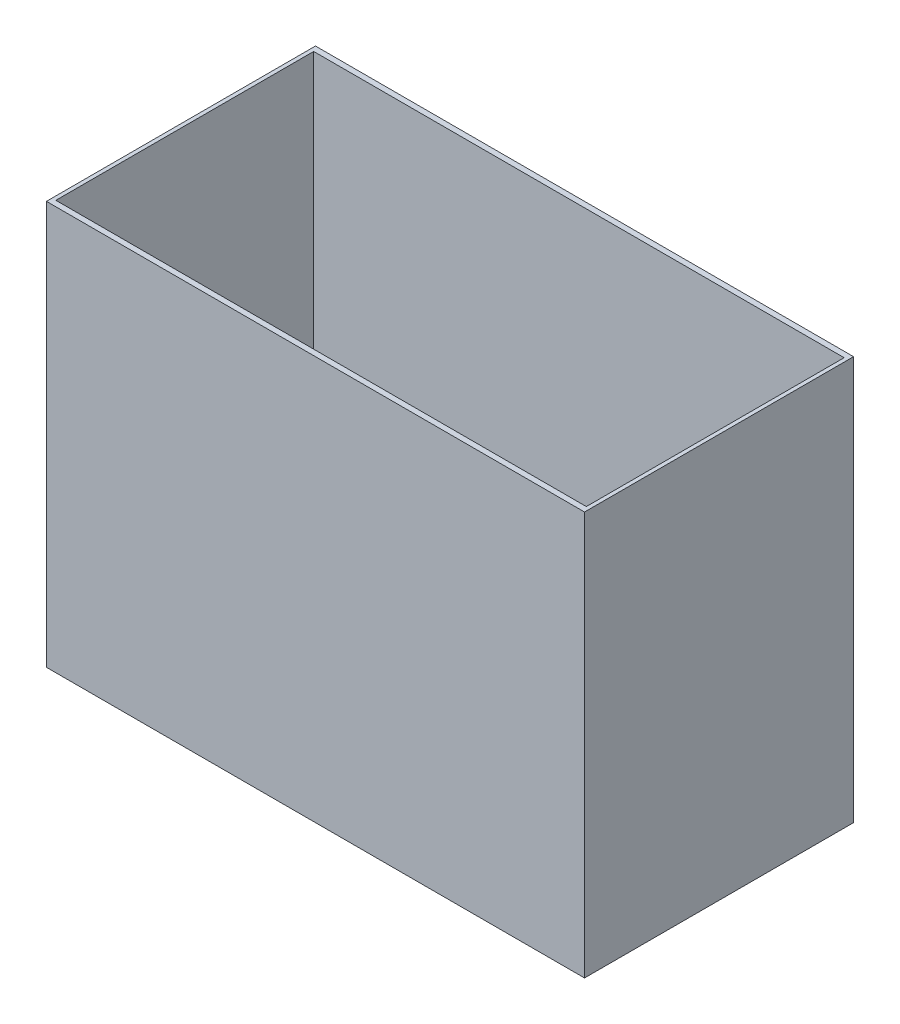
SolidWorks part; units mm, degrees
ref_plane "Front Plane" through (0, 0, 0) normal (0, 0, 1) x (1, 0, 0)
ref_plane "Top Plane" through (0, 0, 0) normal (0, 1, 0) x (1, 0, 0)
ref_plane "Right Plane" through (0, 0, 0) normal (1, 0, 0) x (0, 0, -1)
other "Bounding Box"
ref_plane "Default Plane" through (-292.1, 0, -139.7) normal (0, 1, 0) x (1, 0, 0)
sketch "Sketch1" plane through (0, 0, 0) normal (0, 1, 0) x (1, 0, 0)
  line L0 (-292.1, -139.7) -> (165.1, -139.7) construction
  line L5 (292.1, 139.7) -> (165.1, 139.7)
  line L6 (292.1, 139.7) -> (292.1, -139.7)
  line L7 (292.1, -139.7) -> (165.1, -139.7)
  line L8 (165.1, 139.7) -> (165.1, -139.7)
  dimension "D1" = 127
extrude "Boss-Extrude1" add sketch "Sketch1" along normal blind 6.35
sketch "Sketch2" plane through (0, 6.35, 0) normal (0, 1, 0) x (1, 0, 0)
  line L0 (-245.9259, -63.5) -> (-55.3589, -63.5) construction
  line L1 (342.9, -120.6497) -> (431.8, -120.6497)
  line L2 (342.9, -120.6497) -> (342.9, -101.5997)
  line L3 (342.9, -101.5997) -> (431.8, -101.5997)
  line L4 (431.8, -120.6497) -> (431.8, -101.5997)
  line L5 (342.9, -120.6497) -> (431.8, -101.5997) construction
  line L6 (342.9, -101.5997) -> (431.8, -120.6497) construction
  line L7 (292.1, 139.7) -> (292.1, -139.7) construction
  line L8 (292.1, 0) -> (165.1, 0) construction
  line L9 (165.1, -139.7) -> (165.1, 139.7) construction
  line L10 (228.6, 0) -> (228.6, 121.6784) construction
  line L11 (114.3, -101.5997) -> (25.4, -120.6497) construction
  line L12 (114.3, -120.6497) -> (25.4, -101.5997) construction
  line L13 (25.4, -120.6497) -> (25.4, -101.5997)
  line L14 (114.3, -101.5997) -> (25.4, -101.5997)
  line L15 (114.3, -120.6497) -> (114.3, -101.5997)
  line L16 (114.3, -120.6497) -> (25.4, -120.6497)
  point P0 (387.35, -111.1247)
  point P17 (69.85, -111.1247)
  dimension "D1" = 19.05
  dimension "D2" = 88.9
  dimension "D3" = 38.0997
  dimension "D4" = 50.8
  dimension "D5" = 63.5
extrude "Boss-Extrude2" [suppressed] add sketch "Sketch2" along normal blind 304.8 separate body contours L2 L1 L4 L3
pattern_linear "LPattern1" [suppressed] count 2 spacing 304.8
pattern_linear "LPattern2" [suppressed] count 2 spacing 215.9
sketch "Sketch3" plane through (0, 0, 0) normal (0, 1, 0) x (1, 0, 0)
  line L1 (-304.8, -152.4) -> (304.8, -152.4)
  line L2 (-304.8, -152.4) -> (-304.8, 152.4)
  line L3 (-304.8, 152.4) -> (304.8, 152.4)
  line L4 (304.8, -152.4) -> (304.8, 152.4)
  line L5 (-304.8, -152.4) -> (304.8, 152.4) construction
  line L6 (-304.8, 152.4) -> (304.8, -152.4) construction
  line L7 (-300.482, -146.05) -> (300.482, -146.05)
  line L8 (-300.482, -146.05) -> (-300.482, 146.05)
  line L9 (-300.482, 146.05) -> (300.482, 146.05)
  line L10 (300.482, -146.05) -> (300.482, 146.05)
  line L11 (-300.482, -146.05) -> (300.482, 146.05) construction
  line L12 (-300.482, 146.05) -> (300.482, -146.05) construction
  point P0 (0, 0)
  point P6 (0, 0)
  dimension "D1" = 609.6
  dimension "D2" = 304.8
  dimension "D3" = 292.1
  dimension "D4" = 600.964
extrude "Boss-Extrude3" add sketch "Sketch3" along normal blind 457.2 separate body
sketch "Sketch4" plane through (0, 6.35, 0) normal (0, 1, 0) x (1, 0, 0)
  circle A2 centre (252.0119, 99.6119) radius 21.0381 construction
  circle A3 centre (252.0119, 99.6119) radius 21.0381
extrude "Cut-Extrude1" cut sketch "Sketch4" against normal through all
mirror "Mirror1" about plane through (0, 0, 0) normal (0, 0, 1) of "Cut-Extrude1"
sketch "Sketch5" plane through (0, 6.35, 0) normal (0, 1, 0) x (1, 0, 0)
  line L0 (292.1, 0) -> (222.2453, 0) construction
  line L1 (292.1, -139.7) -> (292.1, 139.7) construction
  line L2 (292.1, 60.96) -> (267.107, 60.96) construction
  line L3 (292.1, 43.18) -> (285.75, 43.18)
  line L4 (292.1, 43.18) -> (292.1, 17.78)
  line L5 (292.1, 17.78) -> (285.75, 17.78)
  line L6 (285.75, 43.18) -> (285.75, 17.78)
  line L7 (285.75, 78.74) -> (285.75, 104.14)
  line L8 (292.1, 104.14) -> (285.75, 104.14)
  line L9 (292.1, 78.74) -> (292.1, 104.14)
  line L10 (292.1, 78.74) -> (285.75, 78.74)
  line L12 (285.75, 104.14) -> (285.75, 139.7) construction
  line L13 (292.1, 139.7) -> (165.1, 139.7) construction
  line L14 (285.75, 43.18) -> (285.75, 78.74) construction
  line L15 (285.75, 17.78) -> (285.75, -17.78) construction
  line L16 (292.1, -78.74) -> (285.75, -78.74)
  line L17 (292.1, -78.74) -> (292.1, -104.14)
  line L18 (292.1, -104.14) -> (285.75, -104.14)
  line L19 (285.75, -78.74) -> (285.75, -104.14)
  line L20 (285.75, -43.18) -> (285.75, -17.78)
  line L21 (292.1, -17.78) -> (285.75, -17.78)
  line L22 (292.1, -43.18) -> (292.1, -17.78)
  line L23 (292.1, -43.18) -> (285.75, -43.18)
  point P20 (0, 0)
  point P21 (0, 0)
  dimension "D1" = 6.35
  dimension "D2" = 25.4
extrude "Cut-Extrude2" cut sketch "Sketch5" against normal through all
